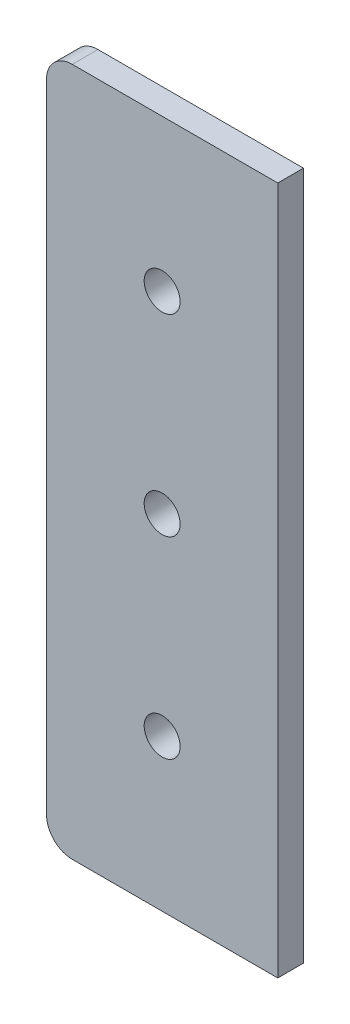
SolidWorks part; units mm, degrees
material "ASTM A36 Steel"
ref_plane "Front Plane" through (0, 0, 0) normal (0, 0, 1) x (1, 0, 0)
ref_plane "Top Plane" through (0, 0, 0) normal (0, 1, 0) x (1, 0, 0)
ref_plane "Right Plane" through (0, 0, 0) normal (1, 0, 0) x (0, 0, -1)
sketch "Sketch1" plane through (0, 0, 0) normal (0, 0, 1) x (1, 0, 0)
  line L0 (-63.3335, 182.4435) -> (-143.3335, 182.4435)
  line L1 (-153.3335, 172.4435) -> (-153.3335, -75.5565)
  line L2 (-143.3335, -85.5565) -> (-63.3335, -85.5565)
  line L3 (-63.3335, -85.5565) -> (-63.3335, 182.4435)
  arc A0 (-143.3335, 182.4435) -> (-153.3335, 172.4435) centre (-143.3335, 172.4435) ccw
  arc A1 (-153.3335, -75.5565) -> (-143.3335, -85.5565) centre (-143.3335, -75.5565) ccw
  circle A2 centre (-108.3335, 48.4435) radius 7
  circle A3 centre (-108.3335, 123.4435) radius 7
  circle A4 centre (-108.3335, -26.5565) radius 7
  dimension "D2" = 14
  dimension "D3" = 14
  dimension "D4" = 14
  dimension "D5" = 134
  dimension "D6" = 75
  dimension "D7" = 75
  dimension "D8" = 45
  dimension "D9" = 45
  dimension "D1" = 268
extrude "Boss-Extrude1" add sketch "Sketch1" along normal blind 10
